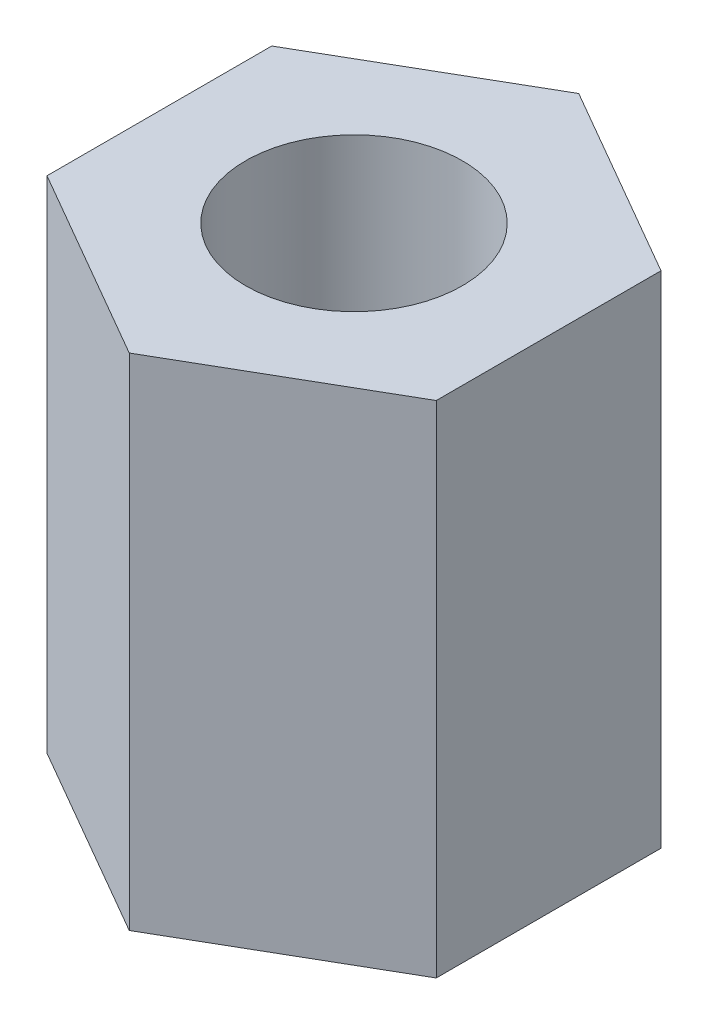
SolidWorks part; units mm, degrees
ref_plane "Front Plane" through (0, 0, 0) normal (0, 0, 1) x (1, 0, 0)
ref_plane "Top Plane" through (0, 0, 0) normal (0, 1, 0) x (1, 0, 0)
ref_plane "Right Plane" through (0, 0, 0) normal (1, 0, 0) x (0, 0, -1)
sketch "Sketch1" plane through (0, 0, 0) normal (0, 1, 0) x (1, 0, 0)
  line L1 (0, -2.6962) -> (2.335, -1.3481)
  line L2 (2.335, -1.3481) -> (2.335, 1.3481)
  line L3 (2.335, 1.3481) -> (0, 2.6962)
  line L4 (0, 2.6962) -> (-2.335, 1.3481)
  line L5 (-2.335, 1.3481) -> (-2.335, -1.3481)
  line L6 (-2.335, -1.3481) -> (0, -2.6962)
  circle A0 centre (0, 0) radius 2.335 construction
  circle A1 centre (0, 0) radius 1.3
  dimension "D2" = 2.6
  dimension "D1" = 4.67
extrude "Boss-Extrude1" add sketch "Sketch1" along normal blind 6
equation "\"Height\"=6"
equation "\"D1@Boss-Extrude1\"=10"
